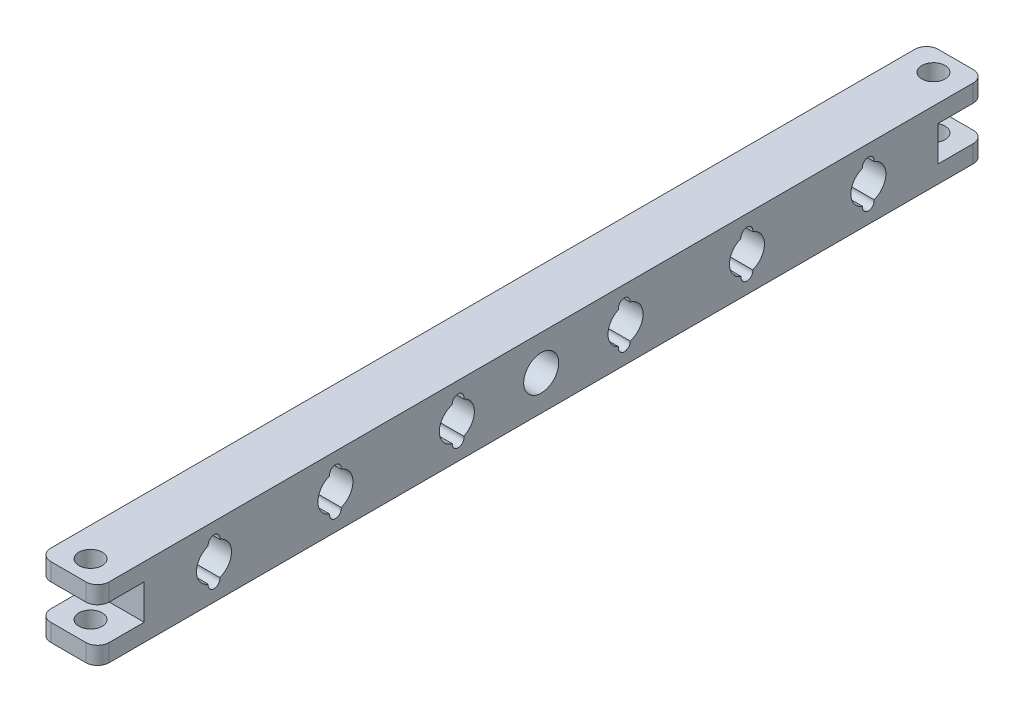
SolidWorks part; units mm, degrees
ref_plane "Front Plane" through (0, 0, 0) normal (0, 0, 1) x (1, 0, 0)
ref_plane "Top Plane" through (0, 0, 0) normal (0, 1, 0) x (1, 0, 0)
ref_plane "Right Plane" through (0, 0, 0) normal (1, 0, 0) x (0, 0, -1)
sketch "Sketch1" plane through (0, 0, 0) normal (1, 0, 0) x (0, 0, -1)
  line L0 (-431.8, 0) -> (431.8, 0) construction
  line L1 (-431.8, -38.1) -> (-431.8, 38.1)
  line L2 (-431.8, 38.1) -> (431.8, 38.1)
  line L3 (431.8, 38.1) -> (431.8, -38.1)
  line L4 (0, 232.9896) -> (0, -232.9896) construction
  line L5 (-431.8, -38.1) -> (431.8, -38.1)
  arc A0 (-362.1471, 17.9917) -> (-362.1471, -17.9917) centre (-355.8859, 0) ccw
  arc A1 (-349.6248, 17.9917) -> (-362.1471, 17.9917) centre (-355.8859, 19.05) ccw
  arc A2 (-230.0671, 17.9917) -> (-230.0671, -17.9917) centre (-223.8059, 0) ccw
  arc A3 (-217.5448, 17.9917) -> (-230.0671, 17.9917) centre (-223.8059, 19.05) ccw
  arc A4 (-96.7289, 18.3813) -> (-96.7289, -18.3813) centre (-91.7259, 0) ccw
  arc A5 (-84.2364, 17.516) -> (-96.7289, 18.3813) centre (-90.4095, 19.0045) ccw
  arc A6 (-349.6248, -17.9917) -> (-349.6248, 17.9917) centre (-355.8859, 0) ccw
  arc A7 (-217.5448, -17.9917) -> (-217.5448, 17.9917) centre (-223.8059, 0) ccw
  arc A8 (-84.2364, -17.516) -> (-84.2364, 17.516) centre (-91.7259, 0) ccw
  arc A9 (84.2364, -17.516) -> (84.2364, 17.516) centre (91.7259, 0) cw
  arc A10 (84.2364, 17.516) -> (96.7289, 18.3813) centre (90.4095, 19.0045) cw
  arc A11 (96.7289, 18.3813) -> (96.7289, -18.3813) centre (91.7259, 0) cw
  arc A12 (217.5448, -17.9917) -> (217.5448, 17.9917) centre (223.8059, 0) cw
  arc A13 (217.5448, 17.9917) -> (230.0671, 17.9917) centre (223.8059, 19.05) cw
  arc A14 (230.0671, 17.9917) -> (230.0671, -17.9917) centre (223.8059, 0) cw
  arc A15 (349.6248, -17.9917) -> (349.6248, 17.9917) centre (355.8859, 0) cw
  arc A16 (349.6248, 17.9917) -> (362.1471, 17.9917) centre (355.8859, 19.05) cw
  arc A17 (362.1471, 17.9917) -> (362.1471, -17.9917) centre (355.8859, 0) cw
  arc A18 (-349.6248, -17.9917) -> (-362.1471, -17.9917) centre (-355.8859, -19.05) cw
  arc A19 (-217.5448, -17.9917) -> (-230.0671, -17.9917) centre (-223.8059, -19.05) cw
  arc A20 (-84.2364, -17.516) -> (-96.7289, -18.3813) centre (-90.4095, -19.0045) cw
  arc A21 (84.2364, -17.516) -> (96.7289, -18.3813) centre (90.4095, -19.0045) ccw
  arc A22 (217.5448, -17.9917) -> (230.0671, -17.9917) centre (223.8059, -19.05) ccw
  arc A23 (349.6248, -17.9917) -> (362.1471, -17.9917) centre (355.8859, -19.05) ccw
  point P4 (0, 0)
  point P11 (0, 0)
  point P54 (-431.8, 0)
  dimension "D4" = 38.1
  dimension "D5" = 12.7
  dimension "D6" = 12.7
  dimension "D7" = 38.1
  dimension "D8" = 38.1
  dimension "D9" = 12.7
  dimension "D1" = 863.6
  dimension "D2" = 38.1
  dimension "D3" = 38.1
  dimension "D10" = 132.08
  dimension "D11" = 132.08
extrude "Boss-Extrude1" add sketch "Sketch1" along normal blind 63.5
sketch "Sketch2" plane through (63.5, 0, 0) normal (1, 0, 0) x (0, 0, -1)
  circle A0 centre (0, 0) radius 19.05
  dimension "D1" = 38.1
extrude "Cut-Extrude1" cut sketch "Sketch2" against normal blind 63.5
sketch "Sketch3" plane through (0, 0, -431.8) normal (0, 0, -1) x (-1, 0, 0)
  line L0 (0, 19.05) -> (-63.5, 19.05)
  line L1 (0, -19.05) -> (-63.5, -19.05)
  line L2 (0, 19.05) -> (0, 38.1)
  line L3 (-63.5, -19.05) -> (-63.5, -38.1)
  line L4 (0, -38.1) -> (0, 38.1)
  line L5 (0, 38.1) -> (-63.5, 38.1)
  line L6 (-63.5, 38.1) -> (-63.5, -38.1)
  line L7 (-63.5, -38.1) -> (0, -38.1)
  line L8 (0, -38.1) -> (0, -19.05)
  line L9 (0, 38.1) -> (-63.5, 38.1)
  line L10 (-63.5, 38.1) -> (-63.5, 19.05)
  line L11 (-63.5, -38.1) -> (0, -38.1)
  dimension "D2" = 19.05
  dimension "D3" = 19.05
  dimension "D1" = 0
extrude "Boss-Extrude2" add sketch "Sketch3" along normal blind 50.8
sketch "Sketch4" plane through (0, 0, 431.8) normal (0, 0, 1) x (1, 0, 0)
  line L0 (0, -19.05) -> (63.5, -19.05)
  line L1 (0, 19.05) -> (63.5, 19.05)
  line L2 (0, -19.05) -> (0, -38.1)
  line L3 (63.5, 19.05) -> (63.5, 38.1)
  line L4 (0, 38.1) -> (0, -38.1)
  line L5 (0, -38.1) -> (63.5, -38.1)
  line L6 (63.5, -38.1) -> (63.5, 38.1)
  line L7 (63.5, 38.1) -> (0, 38.1)
  line L8 (0, 38.1) -> (0, 19.05)
  line L9 (0, -38.1) -> (63.5, -38.1)
  line L10 (63.5, -38.1) -> (63.5, -19.05)
  line L11 (63.5, 38.1) -> (0, 38.1)
  dimension "D2" = 19.05
  dimension "D3" = 19.05
  dimension "D1" = 0
extrude "Boss-Extrude3" add sketch "Sketch4" along normal blind 50.8
sketch "Sketch5" plane through (0, 38.1, 0) normal (0, 1, 0) x (1, 0, 0)
  line L0 (31.75, -482.6) -> (31.75, 482.6) construction
  line L1 (63.5, -482.6) -> (0, -482.6) construction
  line L2 (0, 482.6) -> (63.5, 482.6) construction
  line L3 (-27.0409, 0) -> (90.5409, 0) construction
  circle A0 centre (31.75, 458.429) radius 12.7
  circle A1 centre (31.75, -458.429) radius 12.7
  point P12 (31.75, 0)
  dimension "D1" = 25.4
extrude "Cut-Extrude2" cut sketch "Sketch5" against normal blind 221.742
fillet "Fillet1" radius 12.7 8 edges at (63.5, 28.575, -482.6) (63.5, -28.575, -482.6) (0, 28.575, -482.6) (0, -28.575, -482.6) (0, -28.575, 482.6) (0, 28.575, 482.6) (63.5, -28.575, 482.6) (63.5, 28.575, 482.6)
